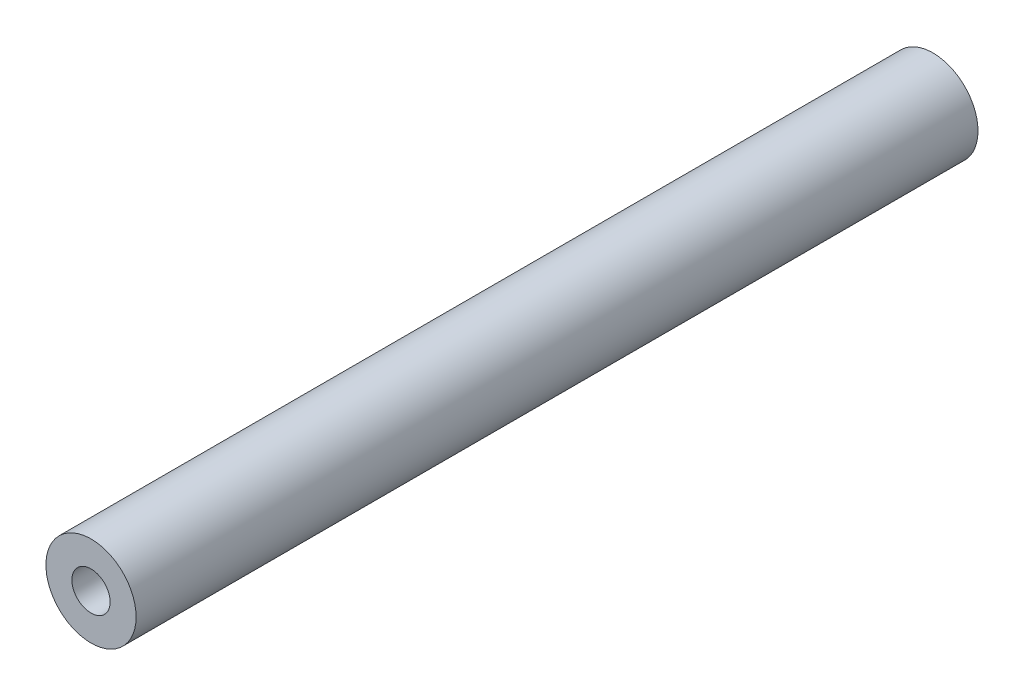
SolidWorks part; units mm, degrees
material "6061-T6 (SS)"
ref_plane "Front Plane" through (0, 0, 0) normal (0, 0, 1) x (1, 0, 0)
ref_plane "Top Plane" through (0, 0, 0) normal (0, 1, 0) x (1, 0, 0)
ref_plane "Right Plane" through (0, 0, 0) normal (1, 0, 0) x (0, 0, -1)
sketch "Sketch1" plane through (0, 0, 0) normal (0, 0, 1) x (1, 0, 0)
  circle A0 centre (0, 0) radius 4.7625
  dimension "D1" = 9.525
extrude "Boss-Extrude1" add sketch "Sketch1" along normal mid plane 88.9
hole_wizard "#10-32 Tapped Hole1" positions "3DSketch1" profile "Sketch2" tap size "#10-32" standard "ANSI Inch"
sketch3d "3DSketch1"
  line L0 (0, 0, 44.45) -> (0, 0, -44.45) construction
  point P0 (0, 0, 44.45)
  point P4 (0, 0, -44.45)
sketch "Sketch2" plane through (0, 0, 44.45) normal (1, 0, 0) x (0, -1, 0)
  line L0 (0, 0) -> (0, 13.1513)
  line L1 (0, 13.1513) -> (2.0193, 11.938)
  line L2 (2.0193, 11.938) -> (2.0193, 0)
  line L5 (2.0193, 0) -> (0, 0)
  line L10 (0, 13.1513) -> (-2.0193, 11.938) construction
  line L11 (0, -6.35) -> (0, 107.95) construction
  dimension "Tap Drill Dia." = 4.0386
  dimension "Tap Drill Depth" = 11.938
  dimension "Drill Angle" = 118
cosmetic thread "Hole Thread1"
cosmetic thread "Hole Thread2"
